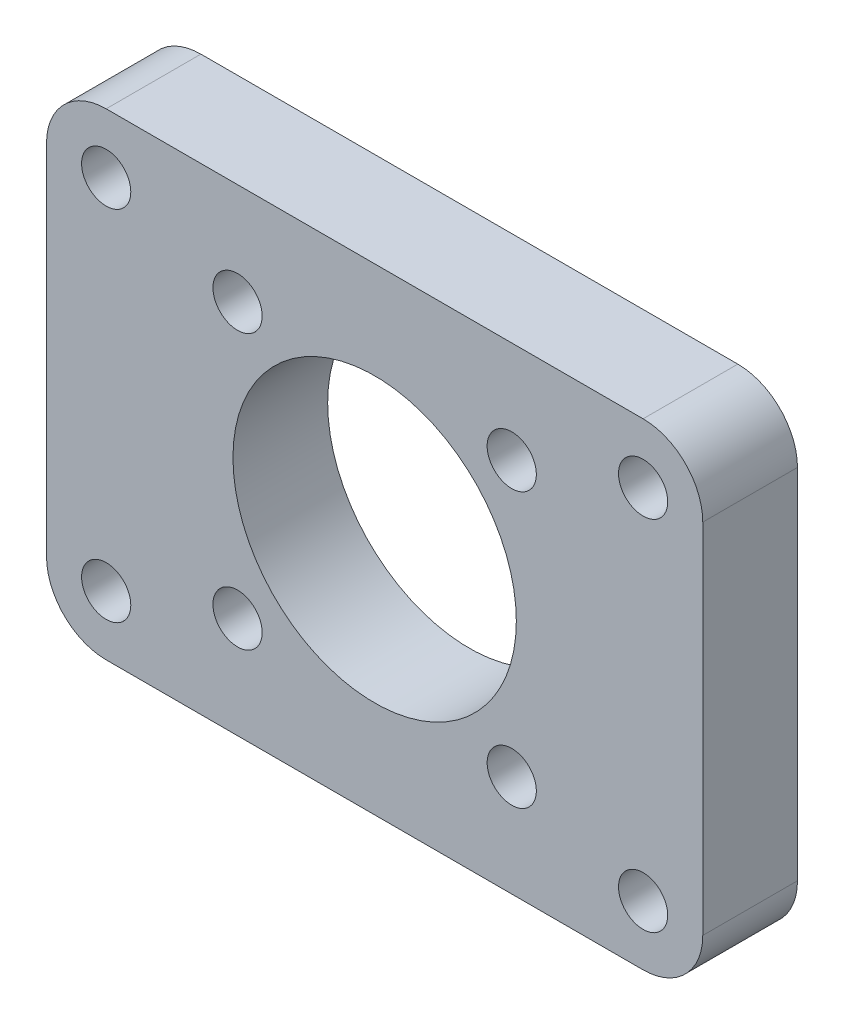
SolidWorks part; units mm, degrees
material "Acrylic (Medium-high impact)"
ref_plane "Front Plane" through (0, 0, 0) normal (0, 0, 1) x (1, 0, 0)
ref_plane "Top Plane" through (0, 0, 0) normal (0, 1, 0) x (1, 0, 0)
ref_plane "Right Plane" through (0, 0, 0) normal (1, 0, 0) x (0, 0, -1)
sketch "Sketch1" plane through (0, 0, 0) normal (0, 0, 1) x (1, 0, 0)
  line L0 (0, 0) -> (0, 16) construction
  line L1 (-22, 16) -> (22, 16)
  line L2 (-22, 16) -> (-22, -16)
  line L3 (-22, -16) -> (22, -16)
  line L4 (22, 16) -> (22, -16)
  line L5 (-9.1924, 9.1924) -> (9.1924, 9.1924) construction
  circle A0 centre (0, 0) radius 9.5
  circle A1 centre (-9.1924, 9.1924) radius 1.65
  circle A2 centre (9.1924, 9.1924) radius 1.65
  circle A3 centre (9.1924, -9.1924) radius 1.65
  circle A4 centre (-9.1924, -9.1924) radius 1.65
  point P19 (0, 0)
  dimension "D1" = 19
  dimension "D2" = 13
  dimension "D3" = 3.3
  dimension "D5" = 16
  dimension "D6" = 32
  dimension "D7" = 44
  dimension "D4" = 4
extrude "Boss-Extrude1" add sketch "Sketch1" along normal blind 6.35
sketch "Sketch2" plane through (0, 0, 6.35) normal (0, 0, 1) x (1, 0, 0)
  line L0 (-18, 12) -> (-18, -12) construction
  line L1 (-22, 16) -> (-22, -16) construction
  line L2 (-18, 0) -> (0, 0) construction
  line L3 (0, 0) -> (0, -12) construction
  line L5 (-18, 16) -> (-18, 12) construction
  line L6 (22, 16) -> (-22, 16) construction
  line L7 (-18, 12) -> (-22, 12) construction
  line L8 (-18, -12) -> (18, -12) construction
  line L10 (18, -12) -> (18, 12) construction
  circle A0 centre (-18, 12) radius 1.65
  circle A1 centre (-18, -12) radius 1.65
  circle A2 centre (18, -12) radius 1.65
  circle A3 centre (18, 12) radius 1.65
  circle A4 centre (0, 0) radius 16 construction
  dimension "D3" = 3.3
  dimension "D2" = 24
  dimension "D4" = 32
  dimension "D1" = 4
extrude "Cut-Extrude1" cut sketch "Sketch2" against normal through all
fillet "Fillet1" radius 4 4 edges at (22, -16, 3.175) (-22, -16, 3.175) (22, 16, 3.175) (-22, 16, 3.175)
